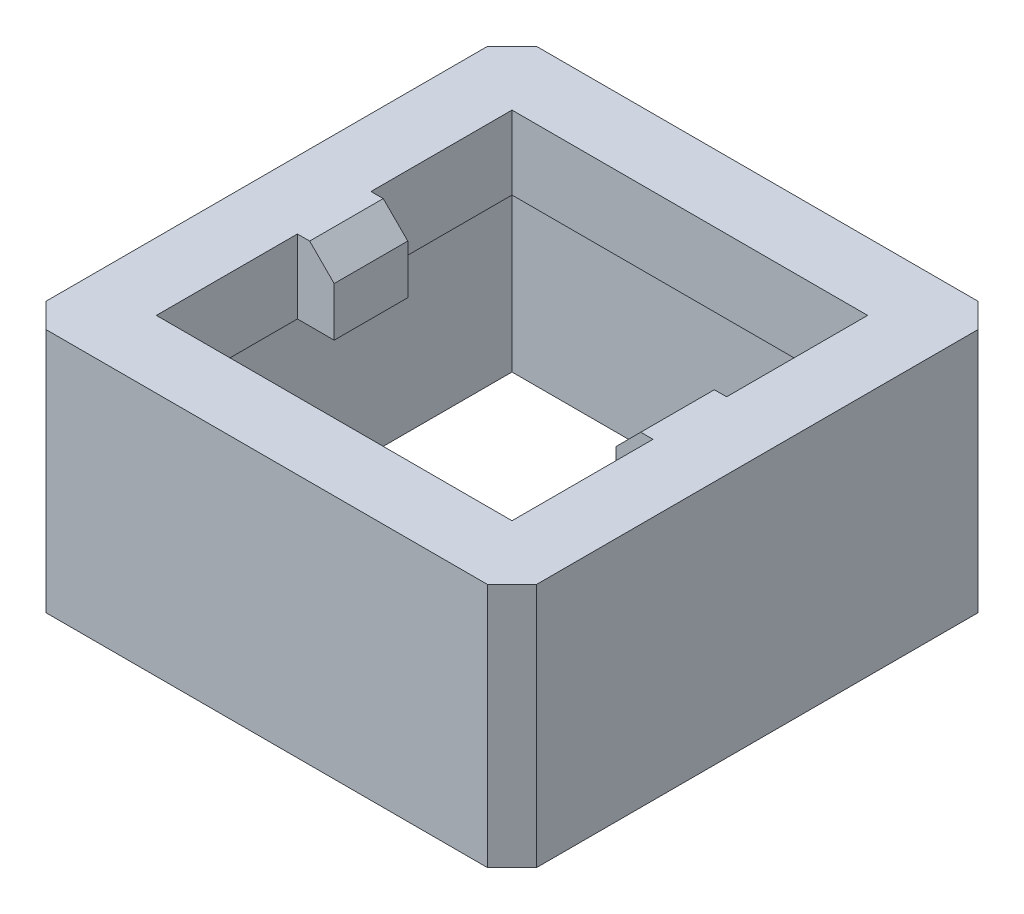
SolidWorks part; units mm, degrees
ref_plane "Front Plane" through (0, 0, 0) normal (0, 0, 1) x (1, 0, 0)
ref_plane "Top Plane" through (0, 0, 0) normal (0, 1, 0) x (1, 0, 0)
ref_plane "Right Plane" through (0, 0, 0) normal (1, 0, 0) x (0, 0, -1)
sketch "Sketch1" plane through (0, 0, 0) normal (0, 1, 0) x (1, 0, 0)
  line L1 (-10, -10) -> (10, -10)
  line L2 (-10, -10) -> (-10, 10)
  line L3 (-10, 10) -> (10, 10)
  line L4 (10, -10) -> (10, 10)
  line L5 (-10, -10) -> (10, 10) construction
  line L6 (-10, 10) -> (10, -10) construction
  point P0 (0, 0)
  dimension "D1" = 20
  dimension "D2" = 20
extrude "Boss-Extrude1" add sketch "Sketch1" along normal blind 3
sketch "Sketch2" plane through (0, 3, 0) normal (0, 1, 0) x (1, 0, 0)
  line L1 (-7.25, -7.25) -> (7.25, -7.25)
  line L2 (-7.25, -7.25) -> (-7.25, 7.25)
  line L3 (-7.25, 7.25) -> (7.25, 7.25)
  line L4 (7.25, -7.25) -> (7.25, 7.25)
  line L5 (-7.25, -7.25) -> (7.25, 7.25) construction
  line L6 (-7.25, 7.25) -> (7.25, -7.25) construction
  point P0 (0, 0)
  dimension "D1" = 14.5
  dimension "D2" = 14.5
extrude "Cut-Extrude1" cut sketch "Sketch2" against normal blind 3
sketch "Sketch3" plane through (0, 3, 0) normal (0, 1, 0) x (1, 0, 0)
  line L0 (7.25, -7.25) -> (7.25, 7.25) construction
  line L1 (7.25, 1.5) -> (5.75, 1.5)
  line L2 (7.25, 1.5) -> (7.25, -1.5)
  line L3 (7.25, -1.5) -> (5.75, -1.5)
  line L4 (5.75, 1.5) -> (5.75, -1.5)
  line L5 (-7.25, 7.25) -> (-7.25, -7.25) construction
  line L6 (-7.25, 1.5) -> (-5.75, 1.5)
  line L7 (-7.25, 1.5) -> (-7.25, -1.5)
  line L8 (-7.25, -1.5) -> (-5.75, -1.5)
  line L9 (-5.75, 1.5) -> (-5.75, -1.5)
  line L10 (7.25, 7.25) -> (-7.25, 7.25) construction
  dimension "D1" = 3
  dimension "D2" = 3
  dimension "D3" = 5.75
  dimension "D4" = 5.75
  dimension "D5" = 1.5
  dimension "D6" = 1.5
extrude "Boss-Extrude2" add sketch "Sketch3" against normal blind 3
chamfer "Chamfer1" distance 1 angle 45 2 edges at (-5.75, 3, 0) (5.75, 3, 0)
sketch "Sketch4" plane through (0, 0, 0) normal (0, -1, 0) x (1, 0, 0)
  line L1 (10, 10) -> (-10, 10)
  line L2 (10, 10) -> (10, -10)
  line L3 (10, -10) -> (-10, -10)
  line L4 (-10, 10) -> (-10, -10)
  line L5 (8, 8) -> (-8, 8)
  line L6 (8, 8) -> (8, -8)
  line L7 (8, -8) -> (-8, -8)
  line L8 (-8, 8) -> (-8, -8)
  dimension "D1" = 2
  dimension "D2" = 2
  dimension "D3" = 2
  dimension "D4" = 2
extrude "Boss-Extrude3" add sketch "Sketch4" along normal blind 7
chamfer "Chamfer2" distance 1 angle 45 4 edges at (-10, -2, 10) (10, -2, 10) (10, -2, -10) (-10, -2, -10)
